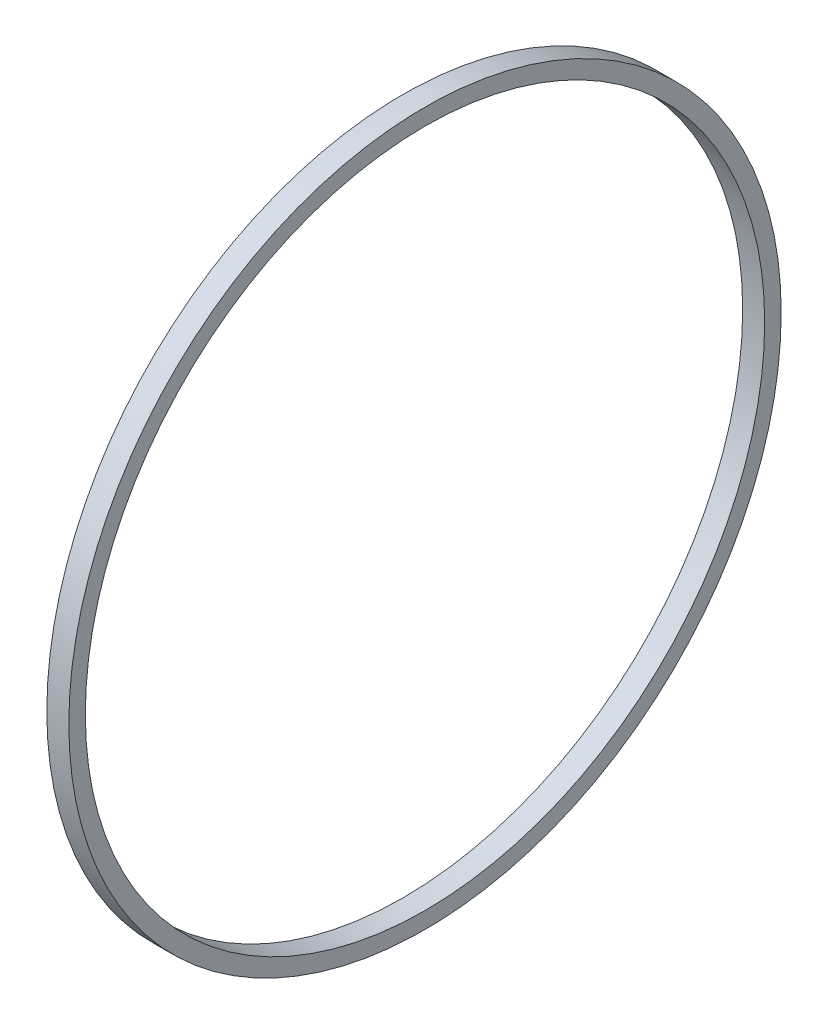
SolidWorks part; units mm, degrees
ref_plane "Front" through (0, 0, 0) normal (0, 0, 1) x (1, 0, 0)
ref_plane "Top" through (0, 0, 0) normal (0, 1, 0) x (1, 0, 0)
ref_plane "Right" through (0, 0, 0) normal (1, 0, 0) x (0, 0, -1)
sketch "Sketch1" plane through (0, 0, 0) normal (0, 0, 1) x (1, 0, 0)
  line L0 (0, 0) -> (0, 98) construction
  line L1 (0, 0) -> (50, 0) construction
  line L2 (-3.175, 102.7625) -> (3.175, 102.7625)
  line L3 (-3.175, 102.7625) -> (-3.175, 98)
  line L4 (-3.175, 98) -> (3.175, 98)
  line L5 (3.175, 102.7625) -> (3.175, 98)
  line L6 (-3.175, 102.7625) -> (3.175, 98) construction
  line L7 (-3.175, 98) -> (3.175, 102.7625) construction
  point P3 (0, 100.3813)
  dimension "D1" = 4.7625
  dimension "D2" = 6.35
  dimension "D3" = 98
  dimension "D4" = 50
revolve "Revolve1" add sketch "Sketch1" angle 360 about L1
